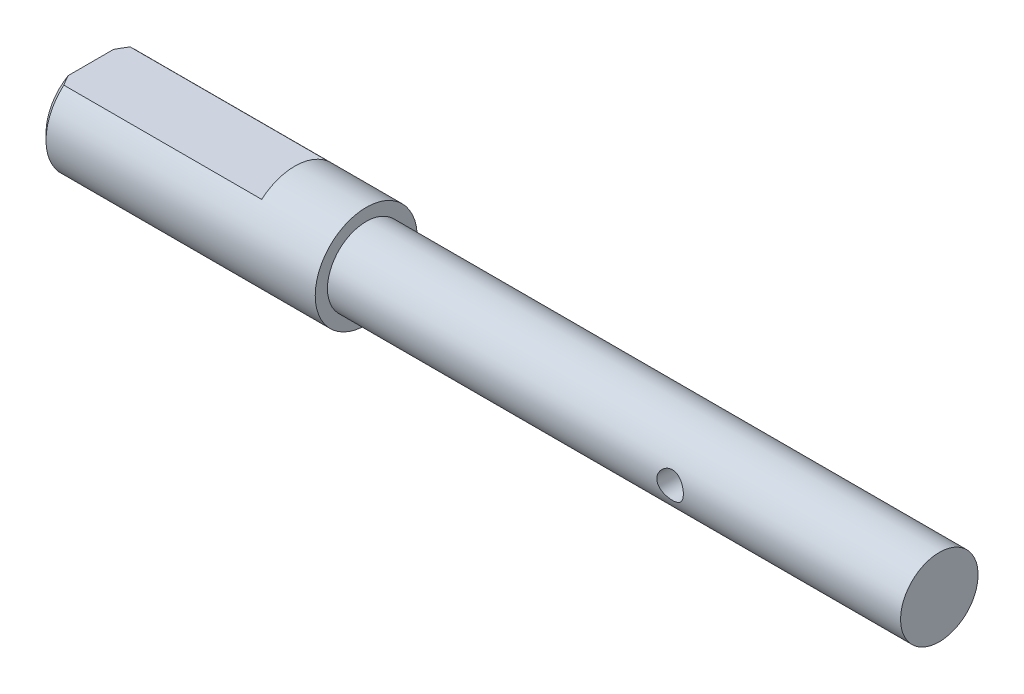
SolidWorks part; units mm, degrees
ref_plane "Front Plane" through (0, 0, 0) normal (0, 0, 1) x (1, 0, 0)
ref_plane "Top Plane" through (0, 0, 0) normal (0, 1, 0) x (1, 0, 0)
ref_plane "Right Plane" through (0, 0, 0) normal (1, 0, 0) x (0, 0, -1)
sketch "Sketch1" plane through (0, 0, 0) normal (0, 0, 1) x (1, 0, 0)
  line L0 (-91.2194, 0) -> (0, 0) construction
  line L1 (0, 0) -> (0, 4.826)
  line L2 (0, 4.826) -> (-71.374, 4.826)
  line L3 (-71.374, 4.826) -> (-71.374, 6.35)
  line L4 (-71.374, 6.35) -> (-105.664, 6.35)
  line L5 (-105.664, 6.35) -> (-105.664, 0)
  line L6 (-105.664, 0) -> (0, 0)
  point P3 (-91.2194, 0)
  dimension "D1" = 9.652
  dimension "D2" = 12.7
  dimension "D3" = 105.664
  dimension "D4" = 71.374
revolve "Revolve1" add sketch "Sketch1" angle 360 about L0
sketch "Sketch2" plane through (0, 0, 0) normal (0, 0, 1) x (1, 0, 0)
  circle A0 centre (-28.702, 0) radius 1.651
  point P2 (0, 0)
  dimension "D1" = 3.302
  dimension "D2" = 28.702
extrude "Cut-Extrude1" cut sketch "Sketch2" against normal through all both and the other way through all
sketch "Sketch4" plane through (-105.664, 0, 0) normal (-1, 0, 0) x (0, 0, 1)
  line L0 (-4.127, 4.826) -> (4.127, 4.826)
  line L1 (0, 6.35) -> (-4.8648, 6.35) construction
  circle A0 centre (0, 0) radius 6.35 construction
  arc A1 (4.127, 4.826) -> (-4.127, 4.826) centre (0, 0) ccw
  point P6 (0, 0)
  point P7 (0, 6.35)
  dimension "D1" = 1.524
extrude "Cut-Extrude2" cut sketch "Sketch4" against normal blind 25.4
chamfer "Chamfer1" distance 0.762 angle 45 1 edges at (-105.664, -6.35, 0)
